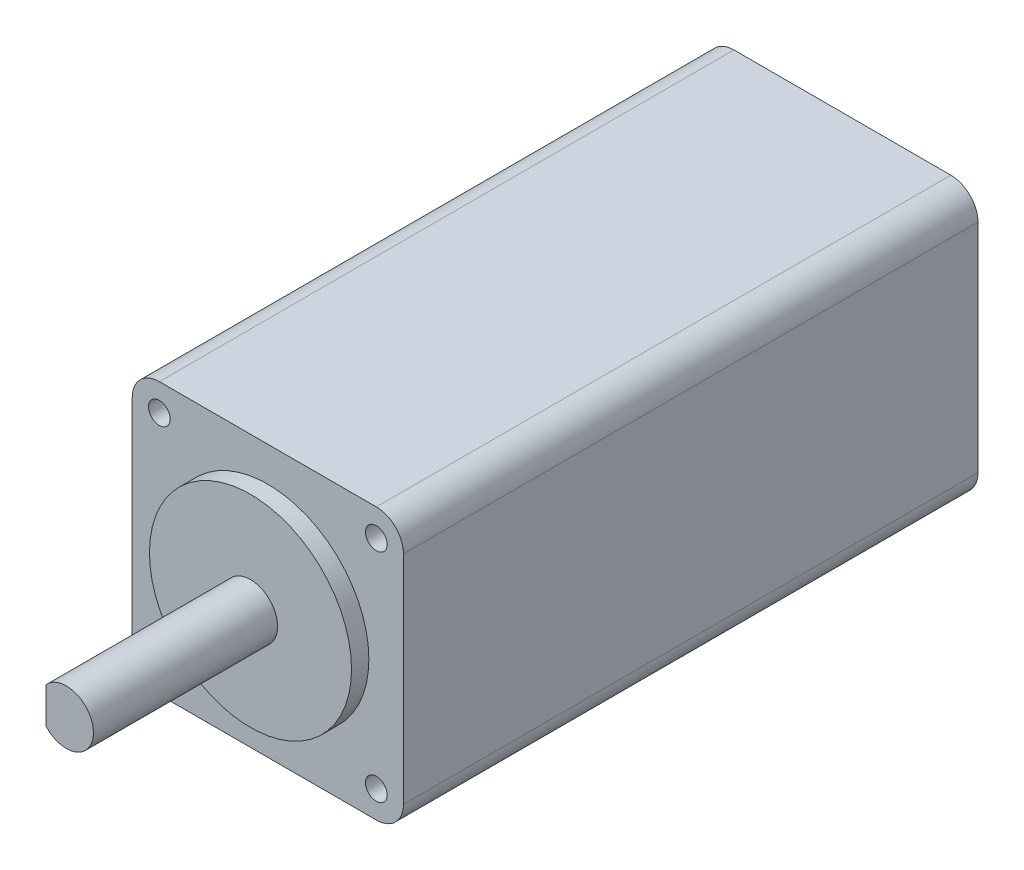
SolidWorks part; units mm, degrees
ref_plane "Front Plane" through (0, 0, 0) normal (0, 0, 1) x (1, 0, 0)
ref_plane "Top Plane" through (0, 0, 0) normal (0, 1, 0) x (1, 0, 0)
ref_plane "Right Plane" through (0, 0, 0) normal (1, 0, 0) x (0, 0, -1)
sketch "Sketch1" plane through (0, 0, 0) normal (0, 0, 1) x (1, 0, 0)
  line L1 (-8, -10) -> (8, -10)
  line L2 (-10, -8) -> (-10, 8)
  line L3 (-8, 10) -> (8, 10)
  line L4 (10, -8) -> (10, 8)
  line L5 (-10, -10) -> (10, 10) construction
  line L6 (-10, 10) -> (10, -10) construction
  arc A0 (10, -8) -> (8, -10) centre (8, -8) cw
  arc A1 (-10, -8) -> (-8, -10) centre (-8, -8) ccw
  arc A2 (-8, 10) -> (-10, 8) centre (-8, 8) ccw
  arc A3 (10, 8) -> (8, 10) centre (8, 8) ccw
  point P0 (0, 0)
  dimension "D3" = 2
  dimension "D1" = 20
  dimension "D2" = 20
extrude "Boss-Extrude1" add sketch "Sketch1" along normal blind 42.37
sketch "Sketch2" plane through (0, 0, 42.37) normal (0, 0, 1) x (1, 0, 0)
  circle A0 centre (0, 0) radius 7.45
  dimension "D1" = 14.9
extrude "Boss-Extrude2" add sketch "Sketch2" along normal blind 1.28
sketch "Sketch3" plane through (0, 0, 43.65) normal (0, 0, 1) x (1, 0, 0)
  line L0 (-1.5, 1.3229) -> (-1.5, -1.3229)
  arc A0 (-1.5, -1.3229) -> (-1.5, 1.3229) centre (0, 0) ccw
  dimension "D1" = 4
  dimension "D2" = 1.5
  dimension "D3" = 1.5
extrude "Boss-Extrude3" add sketch "Sketch3" along normal blind 13.58 contours A0 L0
sketch "Sketch4" plane through (-10, 0, 0) normal (-1, 0, 0) x (0, 0, 1)
  line L0 (3, 5.8) -> (7.9, 5.8)
  line L1 (3, 5.8) -> (3, -5.8)
  line L2 (7.9, 5.8) -> (7.9, -5.8)
  line L3 (3, -5.8) -> (7.9, -5.8)
  line L4 (0, 8) -> (0, -8) construction
  point P6 (0, 0)
  dimension "D1" = 11.6
  dimension "D2" = 4.9
  dimension "D3" = 5.8
  dimension "D4" = 3
extrude "Boss-Extrude4" add sketch "Sketch4" along normal blind 3
hole_wizard "M2 Tapped Hole1" positions "Sketch6" profile "Sketch5" tap size "M2" standard "ISO"
sketch "Sketch6" plane through (0, 0, 42.37) normal (0, 0, 1) x (1, 0, 0)
  line L0 (-10, 8) -> (-10, -8) construction
  line L1 (-8, -10) -> (8, -10) construction
  line L2 (8, 10) -> (-8, 10) construction
  line L3 (10, -8) -> (10, 8) construction
  point P0 (-8, -8)
  point P2 (8, -8)
  point P4 (8, 8)
  point P6 (-8, 8)
  dimension "D1" = 2
  dimension "D2" = 2
  dimension "D3" = 2
  dimension "D4" = 2
  dimension "D5" = 2
  dimension "D6" = 2
  dimension "D7" = 2
  dimension "D8" = 2
sketch "Sketch5" plane through (-8, -8, 42.37) normal (1, 0, 0) x (0, -1, 0)
  line L0 (0, 0) -> (0, 4.4807)
  line L1 (0, 4.4807) -> (0.8, 4)
  line L2 (0.8, 4) -> (0.8, 0)
  line L5 (0.8, 0) -> (0, 0)
  line L10 (0, 4.4807) -> (-0.8, 4) construction
  line L11 (0, -6.35) -> (0, 107.95) construction
  dimension "Tap Drill Dia." = 1.6
  dimension "Tap Drill Depth" = 4
  dimension "Drill Angle" = 118
cosmetic thread "Hole Thread1" parameters "D1"=4, "D2"=2
cosmetic thread "Hole Thread2" parameters "D1"=4, "D2"=2
cosmetic thread "Hole Thread3" parameters "D1"=4, "D2"=2
cosmetic thread "Hole Thread4" parameters "D1"=4, "D2"=2
